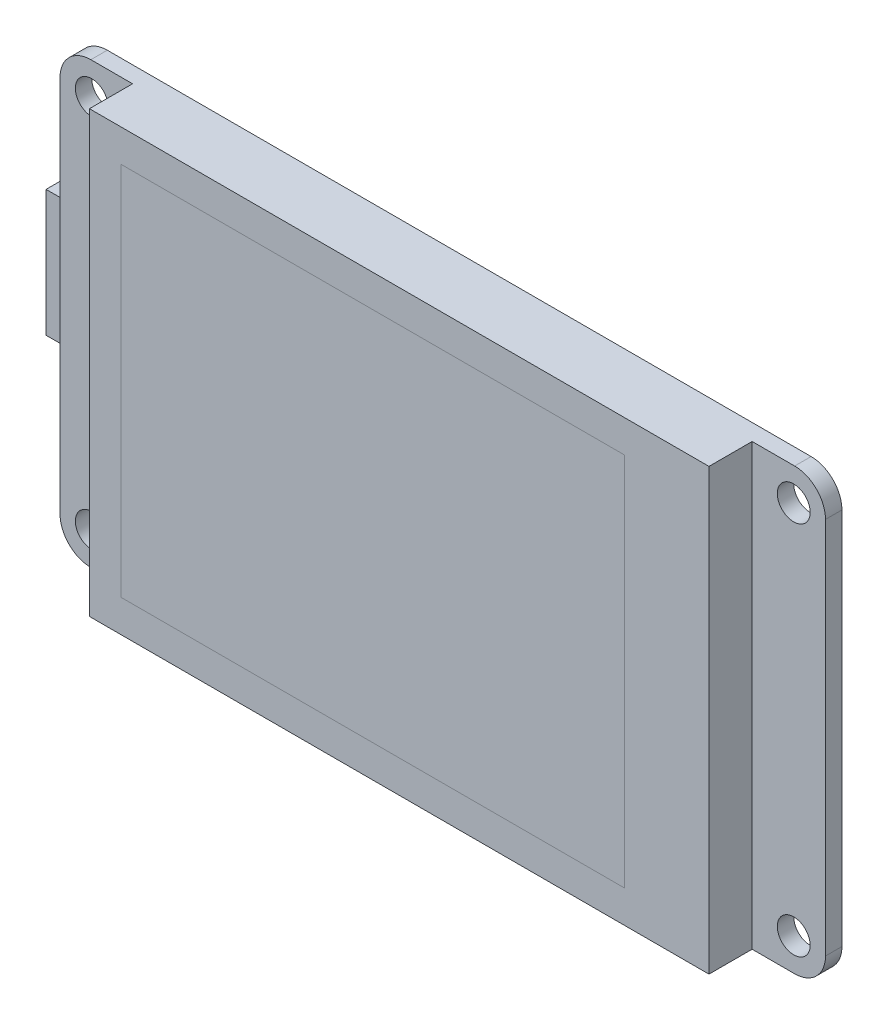
SolidWorks part; units mm, degrees
ref_plane "Front Plane" through (0, 0, 0) normal (0, 0, 1) x (1, 0, 0)
ref_plane "Top Plane" through (0, 0, 0) normal (0, 1, 0) x (1, 0, 0)
ref_plane "Right Plane" through (0, 0, 0) normal (1, 0, 0) x (0, 0, -1)
sketch "Sketch1" plane through (0, 0, 0) normal (0, 0, 1) x (1, 0, 0)
  line L1 (37.25, -21.4) -> (-37.25, -21.4)
  line L2 (37.25, -21.4) -> (37.25, 21.4)
  line L3 (37.25, 21.4) -> (-37.25, 21.4)
  line L4 (-37.25, -21.4) -> (-37.25, 21.4)
  line L5 (37.25, -21.4) -> (-37.25, 21.4) construction
  line L6 (37.25, 21.4) -> (-37.25, -21.4) construction
  point P0 (0, 0)
  dimension "D1" = 74.5
  dimension "D2" = 42.8
extrude "Boss-Extrude1" add sketch "Sketch1" against normal blind 1.6002
sketch "Sketch2" plane through (0, 0, 0) normal (0, 0, 1) x (1, 0, 0)
  line L0 (37.25, 21.4) -> (-37.25, 21.4) construction
  line L1 (30.11, -21.4) -> (-30.19, -21.4)
  line L2 (30.11, -21.4) -> (30.11, 21.4)
  line L3 (30.11, 21.4) -> (-30.19, 21.4)
  line L4 (-30.19, -21.4) -> (-30.19, 21.4)
  line L5 (30.11, -21.4) -> (-30.19, 21.4) construction
  line L6 (30.11, 21.4) -> (-30.19, -21.4) construction
  line L7 (0.8801, 0) -> (-0.8801, 0) construction
  line L8 (37.25, -21.4) -> (37.25, 21.4) construction
  line L9 (-37.25, 21.4) -> (-37.25, -21.4) construction
  point P0 (-0.04, 0)
  dimension "D1" = 60.3
  dimension "D2" = 7.14
  dimension "D3" = 7.06
extrude "Boss-Extrude2" add sketch "Sketch2" along normal blind 4.2
sketch "Sketch3" plane through (0, 0, 4.2) normal (0, 0, 1) x (1, 0, 0)
  line L0 (3.1901, 0) -> (-3.1901, 0) construction
  line L1 (21.89, -18.25) -> (-27.11, -18.25)
  line L2 (21.89, -18.25) -> (21.89, 18.25)
  line L3 (21.89, 18.25) -> (-27.11, 18.25)
  line L4 (-27.11, -18.25) -> (-27.11, 18.25)
  line L5 (21.89, -18.25) -> (-27.11, 18.25) construction
  line L6 (21.89, 18.25) -> (-27.11, -18.25) construction
  line L8 (-37.25, 21.4) -> (-37.25, -21.4) construction
  point P0 (-2.61, 0)
  dimension "D1" = 49
  dimension "D2" = 36.5
  dimension "D3" = 10.14
split line "Split Line1"
hole_wizard "Ø3.2 (3.2) Diameter Hole1" positions "Sketch5" profile "Sketch4" hole size "Ø3.2" standard "ANSI Metric" end condition through all
sketch "Sketch5" plane through (0, 0, 0) normal (0, 0, 1) x (1, 0, 0)
  line L1 (34.16, -18.245) -> (-34.16, -18.245)
  line L2 (34.16, -18.245) -> (34.16, 18.245)
  line L3 (34.16, 18.245) -> (-34.16, 18.245)
  line L4 (-34.16, -18.245) -> (-34.16, 18.245)
  line L5 (34.16, -18.245) -> (-34.16, 18.245) construction
  line L6 (34.16, 18.245) -> (-34.16, -18.245) construction
  line L7 (0, -3.1901) -> (0, 3.1901) construction
  line L8 (3.1901, 0) -> (-3.1901, 0) construction
  point P3 (-34.16, 18.245)
  point P30 (34.16, -18.245)
  point P31 (34.16, 18.245)
  point P32 (-34.16, -18.245)
  point P36 (0, 0)
  dimension "D1" = 36.49
  dimension "D2" = 68.32
sketch "Sketch4" plane through (-34.16, 18.245, 0) normal (1, 0, 0) x (0, -1, 0)
  line L0 (0, 0) -> (0, 1.6002)
  line L1 (0, 1.6002) -> (1.6, 1.6002)
  line L2 (1.6, 1.6002) -> (1.6, 0)
  line L5 (1.6, 0) -> (0, 0)
  line L11 (0, -6.35) -> (0, 107.95) construction
  dimension "Thru Hole Dia." = 3.2
  dimension "Thru Hole Depth" = 1.6002
fillet "Fillet1" radius 3 4 edges at (37.25, 21.4, -0.8001) (37.25, -21.4, -0.8001) (-37.25, -21.4, -0.8001) (-37.25, 21.4, -0.8001)
sketch "Sketch6" plane through (0, 0, -1.6002) normal (0, 0, -1) x (-1, 0, 0)
  line L0 (3.1901, 0) -> (-3.1901, 0) construction
  line L1 (29.25, -7.5) -> (37.25, -7.5)
  line L2 (29.25, -7.5) -> (29.25, 7.5)
  line L3 (29.25, 7.5) -> (37.25, 7.5)
  line L4 (37.25, -7.5) -> (37.25, 7.5)
  line L5 (29.25, -7.5) -> (37.25, 7.5) construction
  line L6 (29.25, 7.5) -> (37.25, -7.5) construction
  line L7 (37.25, 18.4) -> (37.25, -18.4) construction
  point P0 (33.25, 0)
  dimension "D1" = 15
  dimension "D2" = 8
extrude "Boss-Extrude3" add sketch "Sketch6" along normal blind 6.25
sketch "Sketch7" plane through (-37.25, 0, 0) normal (-1, 0, 0) x (0, 0, 1)
  line L0 (6.6276, 0) -> (-6.6276, 0) construction
  line L1 (-2.1402, -6.15) -> (-7.8402, -6.15)
  line L2 (-2.1402, -6.15) -> (-2.1402, 6.15)
  line L3 (-2.1402, 6.15) -> (-7.8402, 6.15)
  line L4 (-7.8402, -6.15) -> (-7.8402, 6.15)
  line L5 (-2.1402, -6.15) -> (-7.8402, 6.15) construction
  line L6 (-2.1402, 6.15) -> (-7.8402, -6.15) construction
  line L7 (-7.8502, -7.5) -> (-7.8502, 7.5) construction
  point P0 (-4.9902, 0)
  dimension "D1" = 12.3
  dimension "D2" = 5.7
  dimension "D3" = 0.01
extrude "Boss-Extrude4" add sketch "Sketch7" along normal blind 3.5
sketch "Sketch8" plane through (0, 0, -1.6002) normal (0, 0, -1) x (-1, 0, 0)
  line L0 (34.25, -21.4) -> (-34.25, -21.4) construction
  line L1 (23.45, -21.4) -> (8.55, -21.4)
  line L2 (23.45, -21.4) -> (23.45, -6.65)
  line L3 (23.45, -6.65) -> (8.55, -6.65)
  line L4 (8.55, -21.4) -> (8.55, -6.65)
  line L5 (23.45, -21.4) -> (8.55, -6.65) construction
  line L6 (23.45, -6.65) -> (8.55, -21.4) construction
  line L7 (37.25, -7.5) -> (37.25, -18.4) construction
  point P0 (16, -14.025)
  dimension "D1" = 14.9
  dimension "D2" = 14.75
  dimension "D3" = 13.8
extrude "Boss-Extrude5" add sketch "Sketch8" along normal blind 2.15
sketch "Sketch9" plane through (0, -21.4, 0) normal (0, -1, 0) x (1, 0, 0)
  line L0 (-8.55, -3.7502) -> (-23.45, -3.7502) construction
  line L1 (-20.35, -3.7402) -> (-9.32, -3.7402)
  line L2 (-20.35, -3.7402) -> (-20.35, -2.6402)
  line L3 (-20.35, -2.6402) -> (-9.32, -2.6402)
  line L4 (-9.32, -3.7402) -> (-9.32, -2.6402)
  line L5 (-20.35, -3.7402) -> (-9.32, -2.6402) construction
  line L6 (-20.35, -2.6402) -> (-9.32, -3.7402) construction
  line L8 (-23.45, -3.7502) -> (-23.45, -1.6002) construction
  point P0 (-14.835, -3.1902)
  dimension "D1" = 11.03
  dimension "D2" = 1.1
  dimension "D3" = 0.01
  dimension "D4" = 3.1
extrude "Boss-Extrude6" add sketch "Sketch9" along normal blind 2.5
